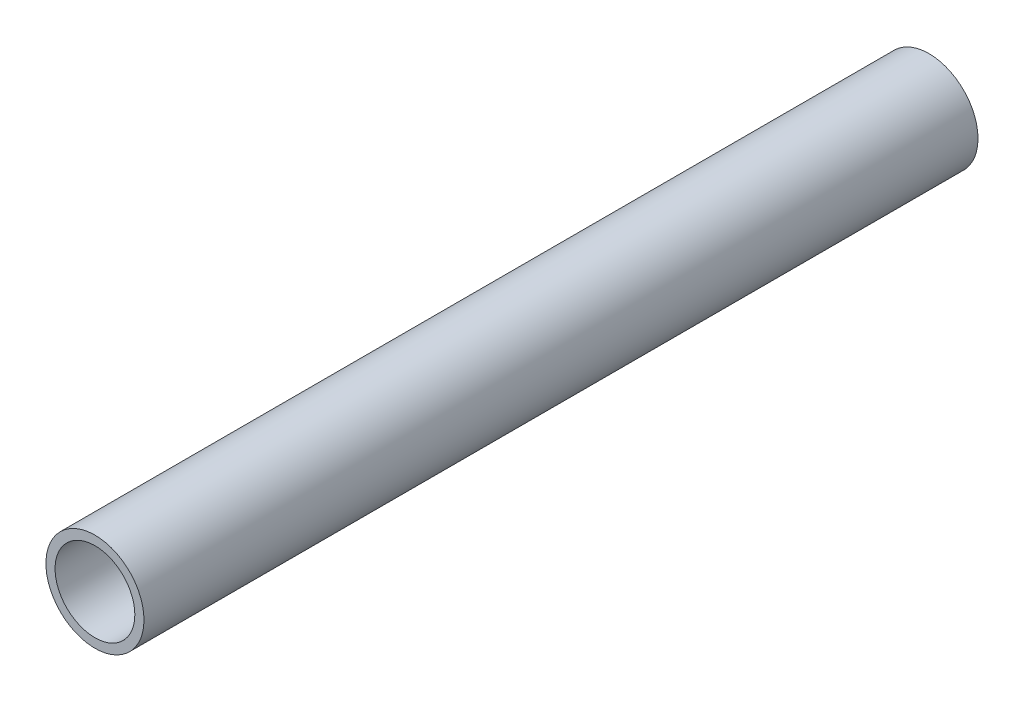
SolidWorks part; units mm, degrees
material "AISI 316 Annealed Stainless Steel Bar (SS)"
ref_plane "Front Plane" through (0, 0, 0) normal (0, 0, 1) x (1, 0, 0)
ref_plane "Top Plane" through (0, 0, 0) normal (0, 1, 0) x (1, 0, 0)
ref_plane "Right Plane" through (0, 0, 0) normal (1, 0, 0) x (0, 0, -1)
sketch "Sketch1" plane through (0, 0, 0) normal (0, 0, 1) x (1, 0, 0)
  circle A0 centre (0, 0) radius 4.7625
  circle A1 centre (0, 0) radius 3.8735
  dimension "D1" = 9.525
  dimension "D2" = 7.747
extrude "Boss-Extrude1" add sketch "Sketch1" along normal blind 81
